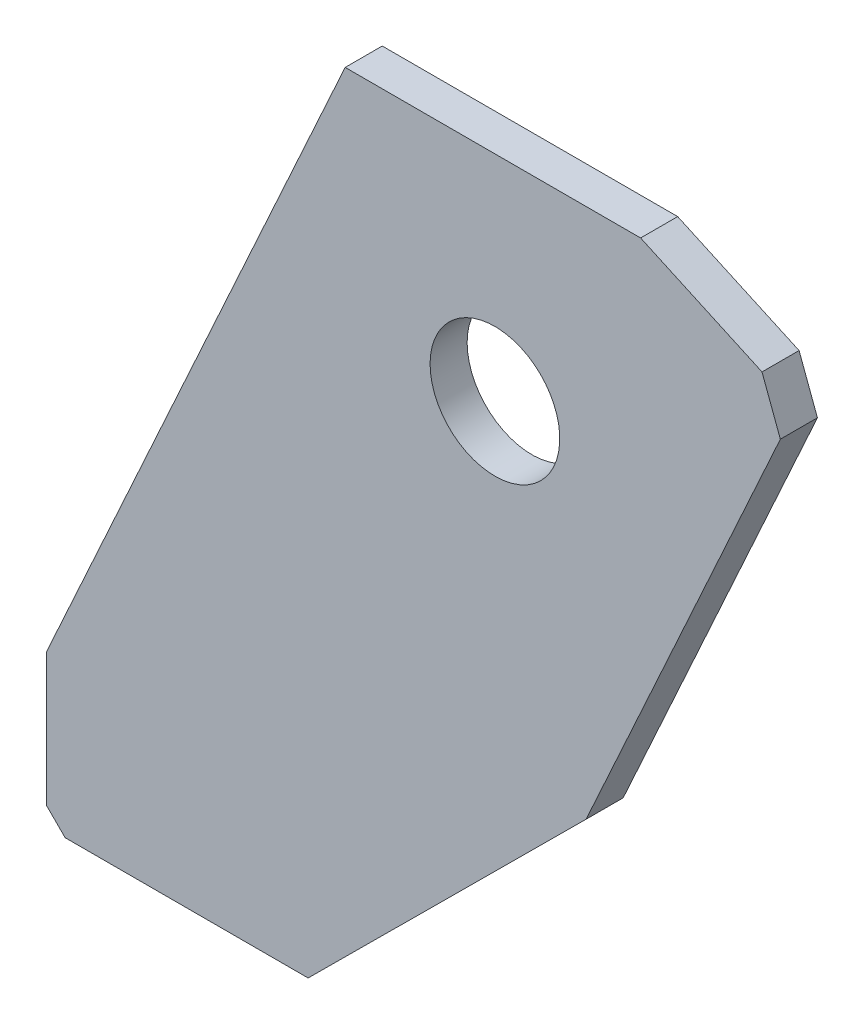
SolidWorks part; units mm, degrees
material "ASTM A36 Steel"
ref_plane "Front Plane" through (0, 0, 0) normal (0, 0, 1) x (1, 0, 0)
ref_plane "Top Plane" through (0, 0, 0) normal (0, 1, 0) x (1, 0, 0)
ref_plane "Right Plane" through (0, 0, 0) normal (1, 0, 0) x (0, 0, -1)
sketch "Sketch1" plane through (0, 0, 0) normal (0, 0, 1) x (1, 0, 0)
  line L0 (-162.5423, -28.6071) -> (-158.5423, -28.6071)
  line L1 (-158.5423, -28.6071) -> (-158.5423, -64.6071)
  line L2 (-12.9367, 5.0022) -> (39.4952, 120.0535)
  line L3 (34.5425, 133.3001) -> (1.7839, 148.229)
  line L4 (-162.5423, -28.6071) -> (-80.2947, 151.8689)
  line L5 (1.7839, 148.229) -> (3.4427, 151.8689)
  line L6 (3.4427, 151.8689) -> (-80.2947, 151.8689)
  line L7 (39.4952, 120.0535) -> (34.5425, 133.3001)
  line L8 (-153.5423, -69.6071) -> (-87.9544, -69.6071)
  line L9 (-12.9367, 5.0022) -> (-87.9544, -69.6071)
  line L10 (-158.5423, -64.6071) -> (-153.5423, -69.6071)
extrude "Boss-Extrude1" add sketch "Sketch1" along normal blind 10
sketch "Sketch2" plane through (0, 0, 10) normal (0, 0, 1) x (1, 0, 0)
  line L0 (1.7839, 148.229) -> (-77.9534, 148.229)
  line L1 (-158.5423, -28.6071) -> (-77.9534, 148.229)
  line L2 (1.7839, 148.229) -> (19.3578, 157.6057)
  line L3 (19.3578, 157.6057) -> (-118.2479, 215.3518)
  line L4 (-118.2479, 215.3518) -> (-258.7649, -56.7841)
  line L5 (-258.7649, -56.7841) -> (-177.6283, -46.1232)
  line L6 (-177.6283, -46.1232) -> (-158.5423, -28.6071)
extrude "Cut-Extrude1" cut sketch "Sketch2" against normal blind 10
sketch "Sketch3" plane through (0, 0, 0) normal (0, 0, -1) x (-1, 0, 0)
  line L0 (158.5423, -28.6071) -> (158.5423, -64.6071) construction
  line L1 (153.5423, -69.6071) -> (87.9544, -69.6071) construction
  circle A0 centre (37.5423, 90.3929) radius 17.5
  dimension "D1" = 35
  dimension "D2" = 121
  dimension "D3" = 160
extrude "Cut-Extrude2" cut sketch "Sketch3" against normal blind 10
